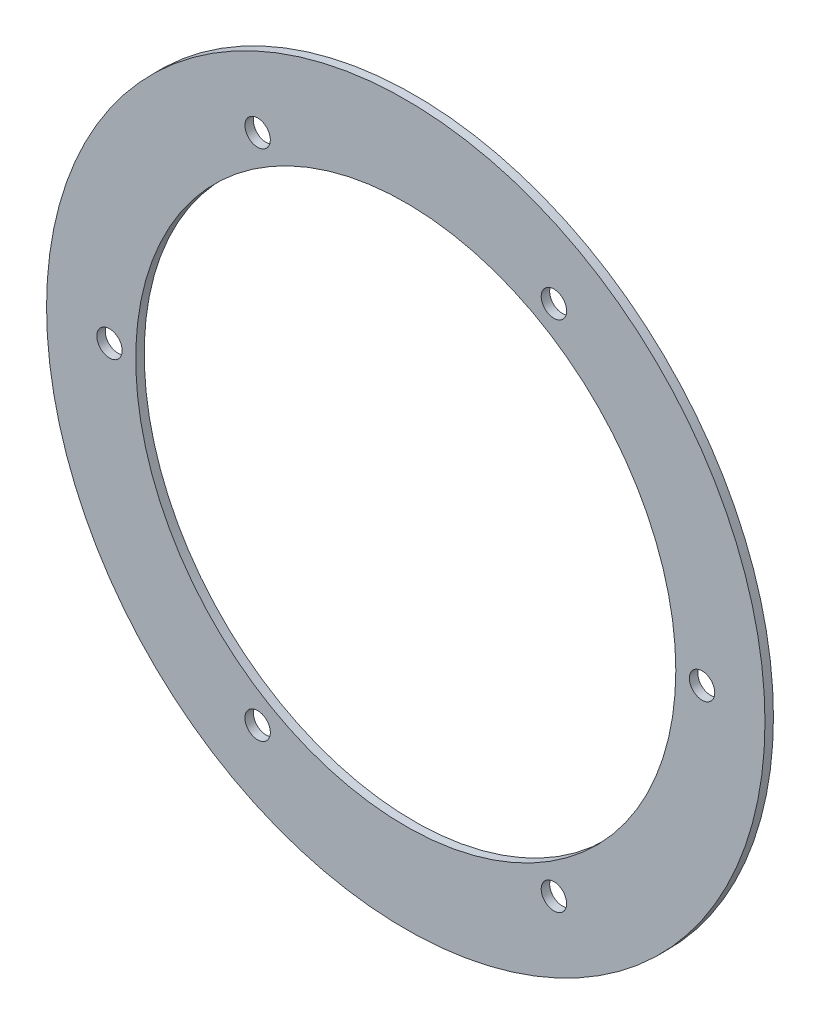
SolidWorks part; units mm, degrees
ref_plane "Ebene vorne" through (0, 0, 0) normal (0, 0, 1) x (1, 0, 0)
ref_plane "Ebene oben" through (0, 0, 0) normal (0, 1, 0) x (1, 0, 0)
ref_plane "Ebene rechts" through (0, 0, 0) normal (1, 0, 0) x (0, 0, -1)
sketch "Skizze1" plane through (0, 0, 0) normal (0, 0, 1) x (1, 0, 0)
  circle A0 centre (0, 0) radius 47.85
  circle A1 centre (0, 0) radius 63.65
  circle A2 centre (0, 0) radius 52.5 construction
extrude "Aufsatz-Linear austragen1" add sketch "Skizze1" along normal blind 1.5
hole_wizard "Durchgangsloch für M41" positions "Skizze2" profile "Skizze3" hole size "M4" standard "DIN" end condition through all
sketch "Skizze2" plane through (0, 0, 1.5) normal (0, 0, 1) x (1, 0, 0)
  circle A0 centre (0, 0) radius 52.5 construction
  point P0 (52.5, 0)
  point P8 (26.25, -45.4663)
  point P9 (-26.25, -45.4663)
  point P10 (-52.5, 0)
  point P11 (-26.25, 45.4663)
  point P12 (26.25, 45.4663)
  dimension "D1" = 6
sketch "Skizze3" plane through (52.5, 0, 1.5) normal (1, 0, 0) x (0, -1, 0)
  line L0 (0, 0) -> (0, 1.5)
  line L1 (0, 1.5) -> (2.25, 1.5)
  line L2 (2.25, 1.5) -> (2.25, 0)
  line L5 (2.25, 0) -> (0, 0)
  line L11 (0, -6.35) -> (0, 107.95) construction
  dimension "Bohrerdurchmesser" = 4.5
  dimension "Bohrungstiefe" = 1.5
